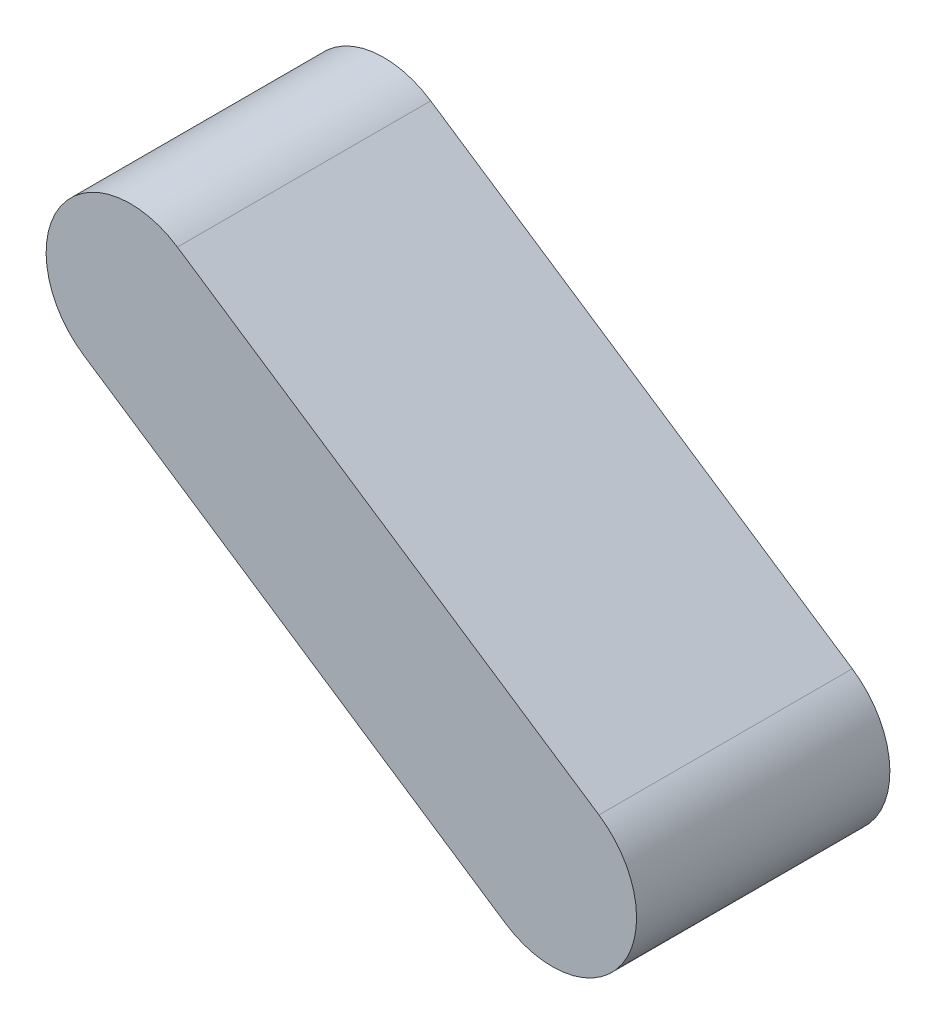
SolidWorks part; units mm, degrees
ref_plane "前视基准面" through (0, 0, 0) normal (0, 0, 1) x (1, 0, 0)
ref_plane "上视基准面" through (0, 0, 0) normal (0, 1, 0) x (1, 0, 0)
ref_plane "右视基准面" through (0, 0, 0) normal (1, 0, 0) x (0, 0, -1)
sketch "草图2" plane through (0, 0, 0) normal (0, 0, 1) x (1, 0, 0)
  line L0 (0, 0) -> (-49.9256, 33.2781) construction
  line L1 (-5.5463, -8.3209) -> (-55.472, 24.9571)
  line L2 (5.5463, 8.3209) -> (-44.3793, 41.599)
  arc A0 (-5.5463, -8.3209) -> (5.5463, 8.3209) centre (0, 0) ccw
  arc A1 (-44.3793, 41.599) -> (-55.472, 24.9571) centre (-49.9256, 33.2781) ccw
  point P2 (-24.9628, 16.639)
  point P7 (0, 0)
  point P8 (0, 0)
  point P9 (0, 0)
  dimension "D1" = 60
  dimension "D2" = 20
extrude "凸台-拉伸1" add sketch "草图2" along normal mid plane 30 contours L1 A1 L2 A0
